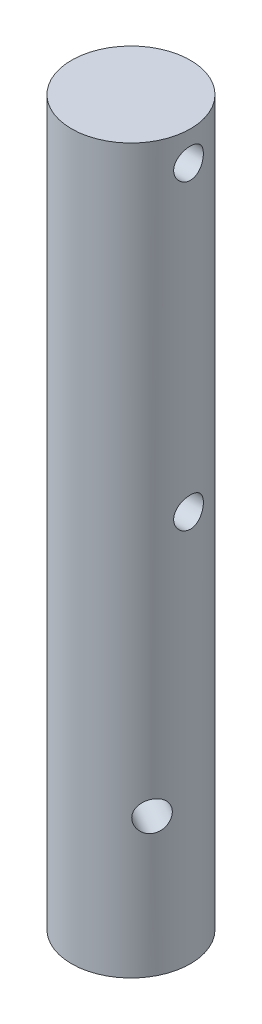
SolidWorks part; units mm, degrees
other "Passive Wheel Axle"
ref_plane "Front Plane" through (0, 0, 0) normal (0, 0, 1) x (1, 0, 0)
ref_plane "Top Plane" through (0, 0, 0) normal (0, 1, 0) x (1, 0, 0)
ref_plane "Right Plane" through (0, 0, 0) normal (1, 0, 0) x (0, 0, -1)
sketch3d "Twelve millimetre axle stock sketch datum points"
  point P0 (-19.0092, -283, -53.2449)
  point P1 (-9.0092, -283, -53.2449)
  point P2 (-19.0092, -283, -63.2449)
ref_plane "Twelve millimetre axle stock sketch plane" through (0, -283, 0) normal (0, 1, 0) x (1, 0, 0)
sketch "Twelve millimetre axle stock sketch" plane through (0, -283, 0) normal (0, 1, 0) x (1, 0, 0)
  circle A0 centre (-19.0092, 53.2449) radius 6
extrude "Twelve millimetre axle stock" add sketch "Twelve millimetre axle stock sketch" along normal blind 73 separate body
sketch3d "Front collar pin sketch datum points"
  point P0 (-26.0092, -213, -53.2449)
  point P1 (-26.0092, -203, -53.2449)
  point P2 (-26.0092, -213, -43.2449)
ref_plane "Front collar pin sketch plane" through (-26.0092, 0, 0) normal (1, 0, 0) x (0, 0, -1)
sketch "Front collar pin sketch" plane through (-26.0092, 0, 0) normal (1, 0, 0) x (0, 0, -1)
  circle A0 centre (53.2449, -213) radius 1.5
extrude "Front collar pin" cut sketch "Front collar pin sketch" along normal blind 14
sketch3d "Rear collar pin sketch datum points"
  point P0 (-26.0092, -243.5, -53.2449)
  point P1 (-26.0092, -233.5, -53.2449)
  point P2 (-26.0092, -243.5, -43.2449)
ref_plane "Rear collar pin sketch plane" through (-26.0092, 0, 0) normal (1, 0, 0) x (0, 0, -1)
sketch "Rear collar pin sketch" plane through (-26.0092, 0, 0) normal (1, 0, 0) x (0, 0, -1)
  circle A0 centre (53.2449, -243.5) radius 1.5
extrude "Rear collar pin" cut sketch "Rear collar pin sketch" along normal blind 14
sketch3d "Hub drive pin sketch datum points"
  point P0 (-25.0714, -269, -56.7449)
  point P1 (-20.0714, -269, -65.4051)
  point P2 (-25.0714, -259, -56.7449)
ref_plane "Hub drive pin sketch plane" through (-43.3748, 0, -25.0424) normal (0.866, 0, 0.5) x (0.5, 0, -0.866)
sketch "Hub drive pin sketch" plane through (-43.3748, 0, -25.0424) normal (0.866, 0, 0.5) x (0.5, 0, -0.866)
  circle A0 centre (36.6068, -269) radius 1.5
extrude "Hub drive pin" cut sketch "Hub drive pin sketch" along normal blind 14
